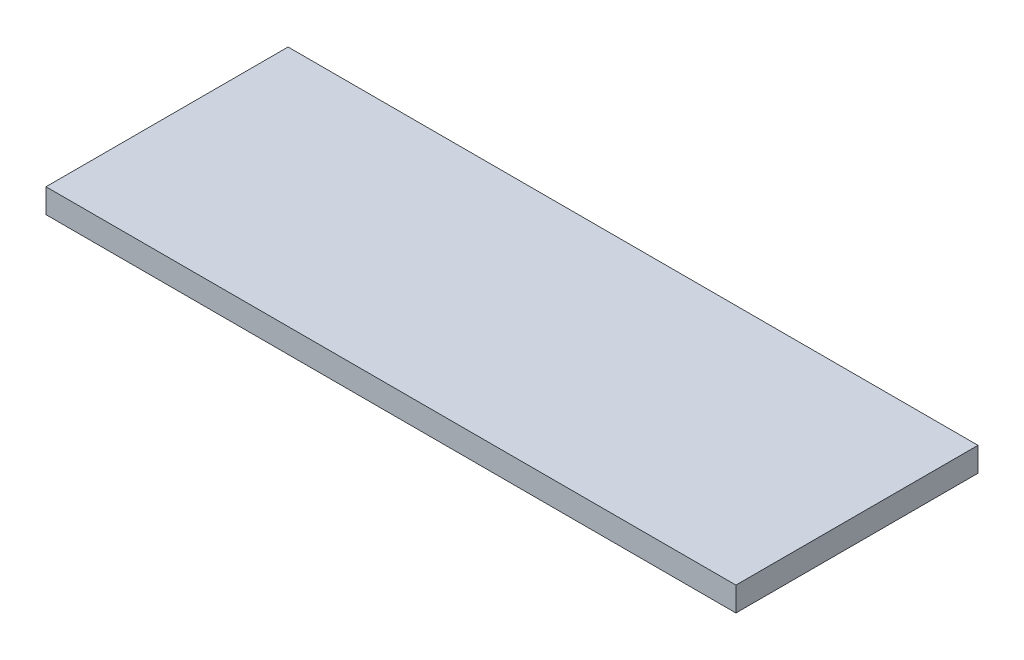
SolidWorks part; units mm, degrees
ref_plane "Front Plane" through (0, 0, 0) normal (0, 0, 1) x (1, 0, 0)
ref_plane "Top Plane" through (0, 0, 0) normal (0, 1, 0) x (1, 0, 0)
ref_plane "Right Plane" through (0, 0, 0) normal (1, 0, 0) x (0, 0, -1)
sketch "Sketch1" plane through (0, 0, 0) normal (0, 0, 1) x (1, 0, 0)
  line L1 (-15.8111, 20.1056) -> (12.6889, 20.1056)
  line L2 (-15.8111, 20.1056) -> (-15.8111, 10.1056)
  line L3 (-15.8111, 10.1056) -> (12.6889, 10.1056)
  line L4 (12.6889, 20.1056) -> (12.6889, 10.1056)
  line L5 (-1.5611, 10.1056) -> (-1.5611, 20.1056) construction
  line L6 (-15.8111, 15.1056) -> (12.6889, 15.1056) construction
  point P104 (-1.5611, 15.1056)
  dimension "D1" = 10
  dimension "D2" = 28.5
extrude "Boss-Extrude1" add sketch "Sketch1" along normal blind 1
move or copy body "Body-Move/Copy1" bodies to move or copy 102 copy no rotation origin (0, 15.1056, 0.25) rotation axis (1, 0, 0) rotation angle 90
